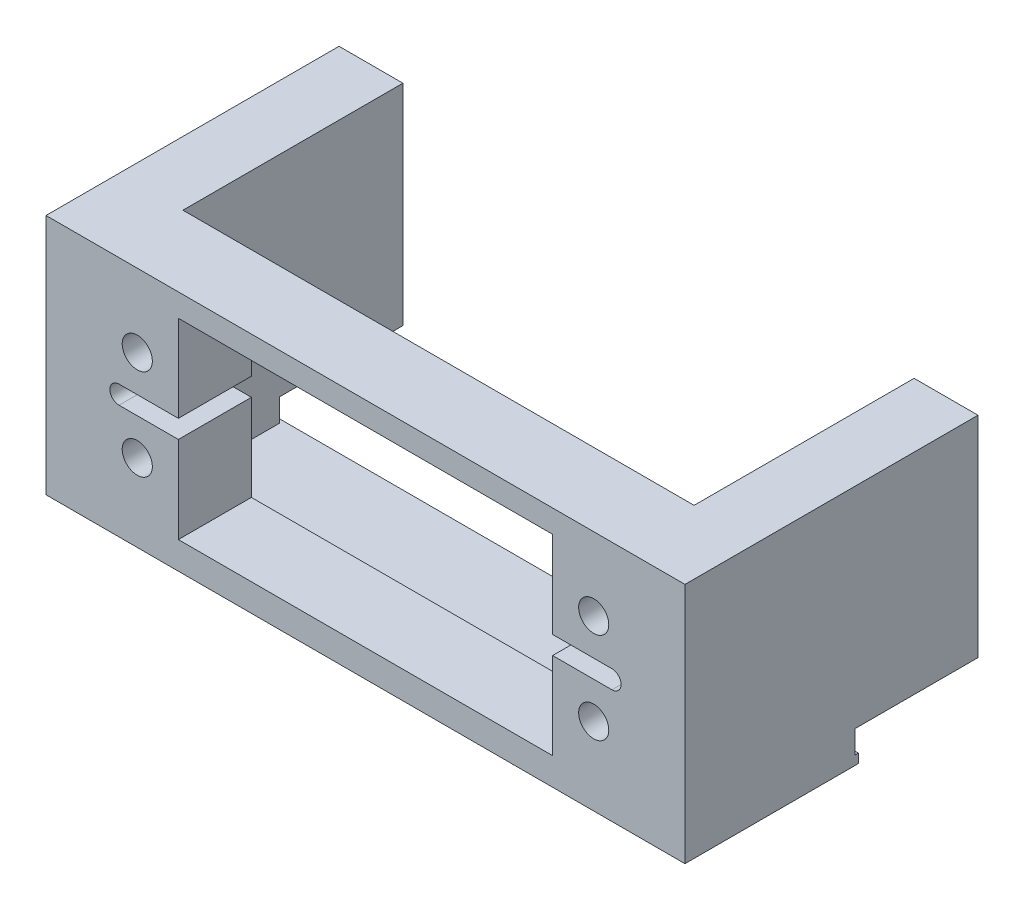
SolidWorks part; units mm, degrees
material "ABS"
ref_plane "前基準面" through (0, 0, 0) normal (0, 0, 1) x (1, 0, 0)
ref_plane "上基準面" through (0, 0, 0) normal (0, 1, 0) x (1, 0, 0)
ref_plane "右基準面" through (0, 0, 0) normal (1, 0, 0) x (0, 0, -1)
sketch "草圖1" plane through (0, 0, 0) normal (0, 0, 1) x (1, 0, 0)
  line L1 (-35, 12.5) -> (35, 12.5)
  line L2 (-35, 12.5) -> (-35, -12.5)
  line L3 (-35, -12.5) -> (35, -12.5)
  line L4 (35, 12.5) -> (35, -12.5)
  line L5 (-35, 12.5) -> (35, -12.5) construction
  line L6 (-35, -12.5) -> (35, 12.5) construction
  point P0 (0, 0)
  dimension "D1" = 70
  dimension "D2" = 25
extrude "填料-伸長1" add sketch "草圖1" along normal blind 8
sketch "草圖2" plane through (0, 0, 0) normal (0, 0, -1) x (-1, 0, 0)
  line L1 (20.5, -11) -> (-20.5, -11)
  line L2 (20.5, -11) -> (20.5, 10)
  line L3 (20.5, 10) -> (-20.5, 10)
  line L4 (-20.5, -11) -> (-20.5, 10)
  line L5 (20.5, -11) -> (-20.5, 10) construction
  line L6 (20.5, 10) -> (-20.5, -11) construction
  line L7 (35, -12.5) -> (-35, -12.5) construction
  line L8 (-35, 12.5) -> (35, 12.5) construction
  point P0 (0, -0.5)
  point P8 (0, 10)
  point P13 (0, 12.5)
  dimension "D1" = 41
  dimension "D2" = 21
  dimension "D4" = 1.5
extrude "除料-伸長1" cut sketch "草圖2" against normal blind 24
sketch "草圖10" plane through (0, 0, 8) normal (0, 0, 1) x (1, 0, 0)
  line L0 (-27, -0.5) -> (-14, -0.5) construction
  line L1 (-20.5, 10) -> (-20.5, -11) construction
  line L2 (-27, 0.5) -> (-14, 0.5)
  line L3 (-27, -1.5) -> (-14, -1.5)
  arc A0 (-27, 0.5) -> (-27, -1.5) centre (-27, -0.5) ccw
  arc A1 (-14, -1.5) -> (-14, 0.5) centre (-14, -0.5) ccw
  point P4 (-20.5, -0.5)
  dimension "D1" = 1
  dimension "D2" = 6.5
extrude "除料-伸長4" cut sketch "草圖10" against normal through all
sketch "草圖5" plane through (0, 0, 8) normal (0, 0, 1) x (1, 0, 0)
  line L0 (-35, -12.5) -> (35, -12.5) construction
  line L1 (-35, 12.5) -> (-28, 12.5)
  line L2 (-35, 12.5) -> (-35, -12.5)
  line L3 (-35, -12.5) -> (-28, -12.5)
  line L4 (-28, 12.5) -> (-28, -12.5)
  dimension "D1" = 7
extrude "填料-伸長2" add sketch "草圖5" against normal blind 24.1 from surface at -8 starting at face at (-12, -0.5, 0)
hole_wizard "M4x0.7 螺紋孔1" positions "草圖7" profile "草圖8" tap size "M4x0.7" standard "Ansi Metric"
sketch "草圖7" plane through (0, 0, -24.1) normal (0, 0, -1) x (-1, 0, 0)
  line L0 (28, -12.5) -> (28, 12.5) construction
  line L1 (28, 12.5) -> (35, 12.5) construction
  point P0 (31.5, 0)
  point P6 (28, 0)
  point P9 (31.5, 12.5)
sketch "草圖8" plane through (-31.5, 0, -24.1) normal (1, 0, 0) x (0, 1, 0)
  line L0 (0, 0) -> (0, 30.9914)
  line L1 (0, 30.9914) -> (1.65, 30)
  line L2 (1.65, 30) -> (1.65, 0)
  line L5 (1.65, 0) -> (0, 0)
  line L10 (0, 30.9914) -> (-1.65, 30) construction
  line L11 (0, -6.35) -> (0, 107.95) construction
  dimension "螺孔鑽直徑" = 3.3
  dimension "螺孔鑽深度" = 30
  dimension "導頭角度" = 118
mirror "鏡射1" about plane through (0, 0, 0) normal (1, 0, 0) of "除料-伸長4", "填料-伸長2", "M4x0.7 螺紋孔1"
sketch "草圖9" plane through (0, -12.5, 0) normal (0, -1, 0) x (1, 0, 0)
  line L0 (28, -24.1) -> (28, 0) construction
  line L1 (35, -24.1) -> (28, -24.1)
  line L2 (35, -24.1) -> (35, -10.6)
  line L3 (35, -10.6) -> (28, -10.6)
  line L4 (28, -24.1) -> (28, -10.6)
  line L5 (0, -14.575) -> (0, 14.575) construction
  line L6 (-35, -10.6) -> (-28, -10.6)
  line L7 (-28, -24.1) -> (-28, -10.6)
  line L8 (-35, -24.1) -> (-28, -24.1)
  line L9 (-35, -24.1) -> (-35, -10.6)
  dimension "D1" = 13.5
extrude "除料-伸長3" cut sketch "草圖9" against normal blind 2
sketch "草圖19" plane through (0, -12.5, 0) normal (0, -1, 0) x (1, 0, 0)
  line L0 (-35, 8) -> (35, 8) construction
  line L1 (35, 8) -> (-35, 8)
  line L2 (35, 8) -> (35, -10.6)
  line L3 (35, -10.6) -> (28, -10.6)
  line L6 (35, -10.6) -> (28, -10.6) construction
  line L7 (28, 0) -> (-28, 0)
  line L9 (-35, 8) -> (-35, -10.6)
  line L10 (-35, -10.6) -> (-28, -10.6)
  line L12 (-28, 0) -> (-28, -10.6)
  line L13 (28, 0) -> (28, -10.6)
extrude "填料-伸長11" add sketch "草圖19" along normal blind 0.5
sketch "草圖20" plane through (0, -13, 0) normal (0, -1, 0) x (1, 0, 0)
  line L1 (35, 8) -> (-35, 8)
  line L2 (35, 8) -> (35, -11)
  line L3 (35, -11) -> (-35, -11)
  line L4 (-35, 8) -> (-35, -11)
  line L6 (28, -10.6) -> (35, -10.6) construction
  line L7 (-35, 8) -> (-35, -10.6) construction
  dimension "D1" = 0.4
extrude "填料-伸長12" add sketch "草圖20" along normal blind 1
hole_wizard "M4x0.7 螺紋孔3" positions "草圖21" profile "草圖22" tap size "M4x0.7" standard "Ansi Metric" end condition up to next
sketch "草圖21" plane through (0, 0, 8) normal (0, 0, 1) x (1, 0, 0)
  line L1 (-25, 4.5) -> (25, 4.5)
  line L2 (-25, 4.5) -> (-25, -5.5)
  line L3 (-25, -5.5) -> (25, -5.5)
  line L4 (25, 4.5) -> (25, -5.5)
  line L5 (-25, 4.5) -> (25, -5.5) construction
  line L6 (-25, -5.5) -> (25, 4.5) construction
  line L7 (20.5, 10) -> (-20.5, 10) construction
  point P2 (25, -5.5)
  point P99 (-25, 4.5)
  point P100 (-25, -5.5)
  point P101 (25, 4.5)
  point P121 (0, -0.5)
  dimension "D1" = 50
  dimension "D2" = 10
  dimension "D3" = 5.5
cosmetic thread "鑽孔螺紋1" parameters "D2"=4
cosmetic thread "鑽孔螺紋2" parameters "D2"=4
cosmetic thread "鑽孔螺紋3" parameters "D2"=4
cosmetic thread "鑽孔螺紋4" parameters "D2"=4
sketch "草圖22" plane through (25, -5.5, 8) normal (1, 0, 0) x (0, -1, 0)
  line L0 (0, 0) -> (0, 8)
  line L1 (0, 8) -> (1.65, 8)
  line L2 (1.65, 8) -> (1.65, 0)
  line L5 (1.65, 0) -> (0, 0)
  line L11 (0, -6.35) -> (0, 107.95) construction
  dimension "貫穿螺孔鑽直徑" = 3.3
  dimension "貫穿螺孔鑽深度" = 8
